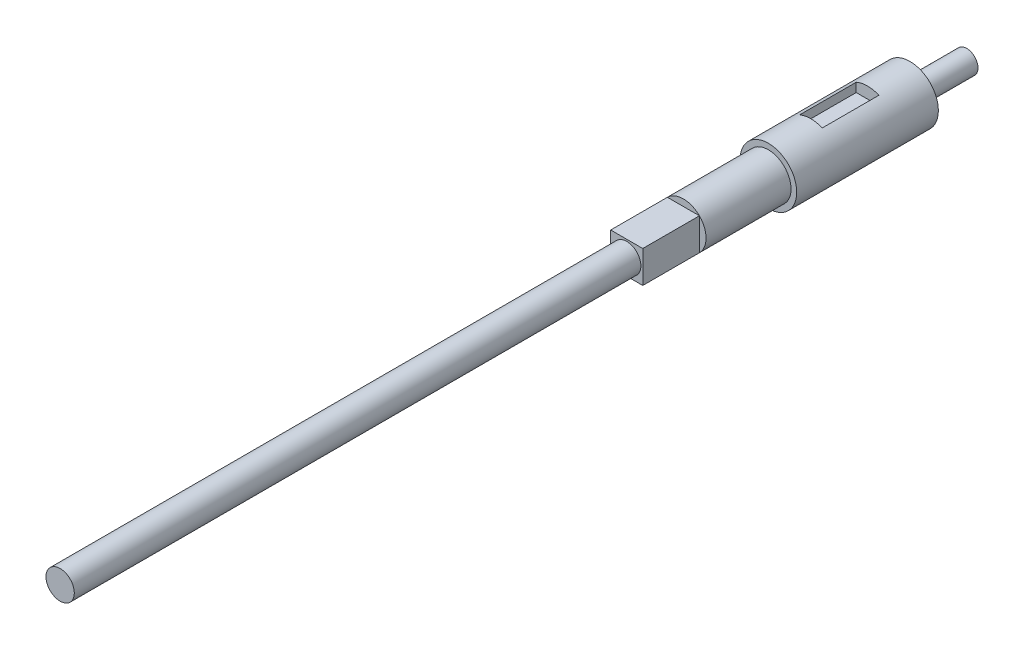
SolidWorks part; units mm, degrees
material "AISI 1020"
ref_plane "Front" through (0, 0, 0) normal (0, 0, 1) x (1, 0, 0)
ref_plane "Top" through (0, 0, 0) normal (0, 1, 0) x (1, 0, 0)
ref_plane "Right" through (0, 0, 0) normal (1, 0, 0) x (0, 0, -1)
sketch "Croquis1" plane through (0, 0, 0) normal (0, 0, 1) x (1, 0, 0)
  circle A0 centre (0, 0) radius 5
  dimension "D1" = 10
extrude "Saliente-Extruir1" add sketch "Croquis1" along normal mid plane 25
sketch "Croquis2" plane through (0, 0, -12.5) normal (0, 0, -1) x (-1, 0, 0)
  circle A0 centre (0, 0) radius 2
  dimension "D1" = 4
extrude "Saliente-Extruir2" add sketch "Croquis2" along normal blind 10
sketch "Croquis3" plane through (0, 0, 12.5) normal (0, 0, 1) x (1, 0, 0)
  circle A0 centre (0, 0) radius 4
  dimension "D1" = 8
extrude "Saliente-Extruir3" add sketch "Croquis3" along normal blind 15
sketch "Croquis4" plane through (0, 0, 27.5) normal (0, 0, 1) x (1, 0, 0)
  line L1 (-2.8284, -2.8284) -> (2.8284, -2.8284)
  line L2 (-2.8284, -2.8284) -> (-2.8284, 2.8284)
  line L3 (-2.8284, 2.8284) -> (2.8284, 2.8284)
  line L4 (2.8284, -2.8284) -> (2.8284, 2.8284)
  line L5 (-2.8284, -2.8284) -> (2.8284, 2.8284) construction
  line L6 (-2.8284, 2.8284) -> (2.8284, -2.8284) construction
  circle A0 centre (0, 0) radius 4 construction
  point P0 (0, 0)
extrude "Saliente-Extruir4" add sketch "Croquis4" along normal blind 10
ref_plane "Plano1" through (0, 5, 0) normal (0, 1, 0) x (1, 0, 0)
sketch "Croquis5" plane through (0, 5, 0) normal (0, 1, 0) x (1, 0, 0)
  line L1 (-2, -5) -> (2, -5)
  line L2 (-2, -5) -> (-2, 5)
  line L3 (-2, 5) -> (2, 5)
  line L4 (2, -5) -> (2, 5)
  line L5 (-2, -5) -> (2, 5) construction
  line L6 (-2, 5) -> (2, -5) construction
  point P0 (0, 0)
  dimension "D1" = 10
  dimension "D2" = 4
extrude "Cortar-Extruir1" cut sketch "Croquis5" against normal blind 2
sketch "Croquis6" plane through (0, 0, 37.5) normal (0, 0, 1) x (1, 0, 0)
  circle A0 centre (0, 0) radius 2.5
  dimension "D1" = 5
extrude "Saliente-Extruir5" add sketch "Croquis6" along normal blind 100
